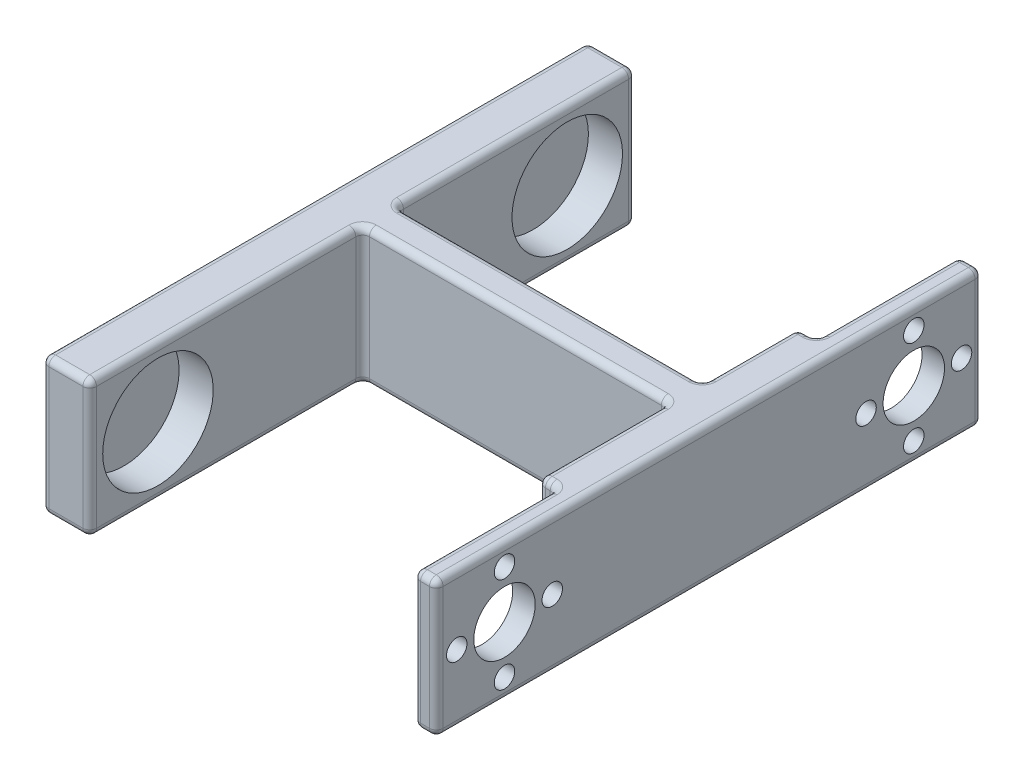
SolidWorks part; units mm, degrees
material "ABS"
ref_plane "Front Plane" through (0, 0, 0) normal (0, 0, 1) x (1, 0, 0)
ref_plane "Top Plane" through (0, 0, 0) normal (0, 1, 0) x (1, 0, 0)
ref_plane "Right Plane" through (0, 0, 0) normal (1, 0, 0) x (0, 0, -1)
sketch "Sketch2" plane through (0, 0, 0) normal (0, 1, 0) x (1, 0, 0)
  line L0 (0, 0) -> (0, -80)
  line L1 (0, -80) -> (6, -80)
  line L2 (6, -80) -> (6, -40)
  line L3 (6, -40) -> (50.8, -40)
  line L4 (50.8, -40) -> (50.8, -80)
  line L5 (50.8, -80) -> (57.8, -80)
  line L6 (57.8, -80) -> (57.8, 0)
  line L7 (57.8, 0) -> (50.8, 0)
  line L8 (50.8, 0) -> (50.8, -35)
  line L9 (50.8, -35) -> (6, -35)
  line L10 (6, -35) -> (6, 0)
  line L11 (6, 0) -> (0, 0)
  dimension "D1" = 80
  dimension "D2" = 6
  dimension "D3" = 40
  dimension "D4" = 44.8
  dimension "D5" = 7
  dimension "D6" = 80
  dimension "D7" = 44.8
extrude "Boss-Extrude1" add sketch "Sketch2" along normal blind 20
sketch "Sketch3" plane through (50.8, 0, 0) normal (-1, 0, 0) x (0, 0, 1)
  line L0 (0, 20) -> (80, 20) construction
  line L1 (80, 20) -> (80, 0) construction
  line L2 (40, 20) -> (40, 0) construction
  circle A0 centre (70, 10) radius 8.1
  circle A1 centre (10, 10) radius 8.1
  dimension "D1" = 16.2
  dimension "D2" = 10
  dimension "D3" = 10
sketch "Sketch4" plane through (0, 0, 0) normal (-1, 0, 0) x (0, 0, 1)
  line L3 (0, 20) -> (80, 20) construction
  line L4 (80, 20) -> (80, 0) construction
  circle A3 centre (70, 10) radius 7 construction
  circle A4 centre (70, 17) radius 1.5
  circle A5 centre (77, 10) radius 1.5
  circle A6 centre (70, 3) radius 1.5
  circle A7 centre (63, 10) radius 1.5
  circle A8 centre (70, 10) radius 4.5
  dimension "D1" = 14
  dimension "D2" = 10
  dimension "D3" = 10
  dimension "D4" = 3
  dimension "D5" = 3
  dimension "D6" = 3
  dimension "D7" = 3
  dimension "D8" = 9
extrude "Cut-Extrude1" cut sketch "Sketch4" against normal blind 10
sketch "Sketch5" plane through (0, 0, 0) normal (-1, 0, 0) x (0, 0, 1)
  line L0 (0, 0) -> (80, 0) construction
  line L1 (59, 0) -> (80, 0)
  line L2 (59, 0) -> (59, 20)
  line L3 (59, 20) -> (80, 20)
  line L4 (80, 0) -> (80, 20)
  dimension "D1" = 21
extrude "Cut-Extrude2" cut sketch "Sketch5" against normal blind 2.7 from offset 3.3 offset against normal yes
ref_plane "Plane1" through (0, 0, 40) normal (0, 0, 1) x (1, 0, 0)
mirror "Mirror1" about plane through (0, 0, 40) normal (0, 0, 1) of "Cut-Extrude1", "Cut-Extrude2"
fillet "Fillet1" radius 1 48 edges at (1.65, 0, 80) (6, 0, 49.5) (28.4, 0, 40) (50.8, 0, 60) (54.3, 0, 80) (57.8, 0, 40) (54.3, 0, 0) (50.8, 0, 17.5) (28.4, 0, 35) (6, 0, 28) (1.65, 0, 0) (0, 0, 40) (4.65, 0, 59) (4.65, 20, 59) (0, 20, 40) (1.65, 20, 0) (6, 20, 28) (28.4, 20, 35) (50.8, 20, 17.5) (54.3, 20, 0) (57.8, 20, 40) (54.3, 20, 80) (50.8, 20, 60) (28.4, 20, 40) (6, 20, 49.5) (1.65, 20, 80) (57.8, 10, 0) (50.8, 10, 0) (0, 10, 0) (50.8, 10, 35) (6, 10, 35) (6, 10, 40) (50.8, 10, 40) (50.8, 10, 80) (57.8, 10, 80) (4.65, 0, 21) (4.65, 20, 21) (3.3, 0, 69.5) (3.3, 0, 10.5) (3.3, 20, 69.5) (3.3, 20, 10.5) (6, 10, 59) (3.3, 10, 59) (3.3, 10, 80) (0, 10, 80) (3.3, 10, 0) (3.3, 10, 21) (6, 10, 21)
extrude "Cut-Extrude3" cut sketch "Sketch3" against normal blind 5
ref_plane "Plane2" through (28.9, 0, 0) normal (-1, 0, 0) x (0, 0, 1)
mirror "Mirror2" about plane through (28.9, 0, 0) normal (-1, 0, 0) of bodies 110
delete or keep bodies "Body-Delete/Keep 1" type delete bodies bodies 110
